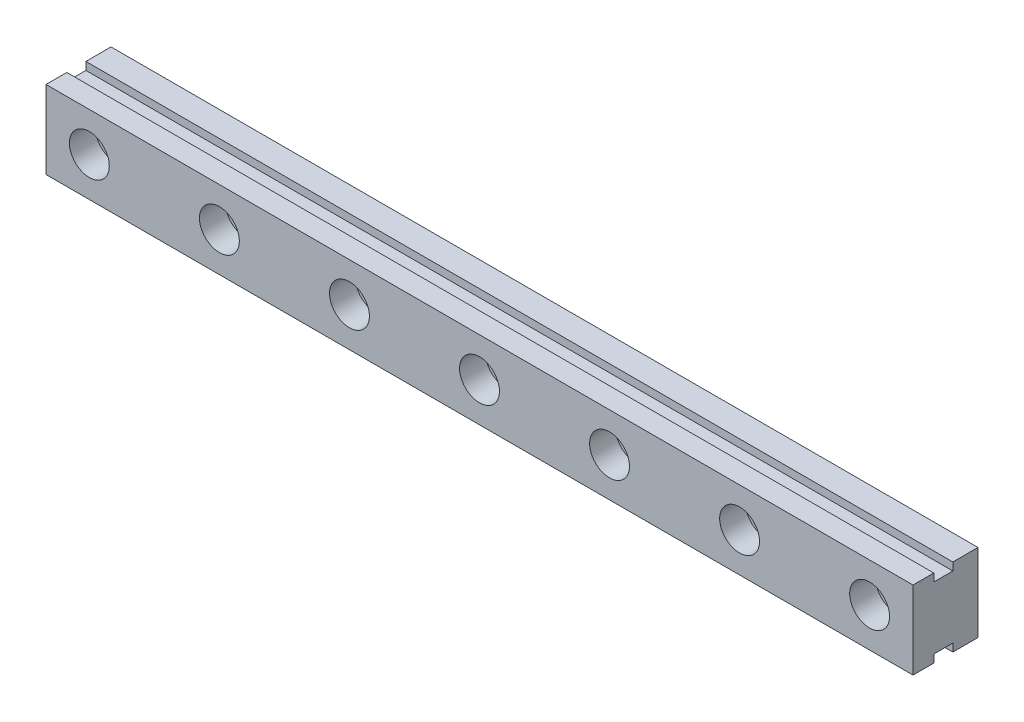
SolidWorks part; units mm, degrees
ref_plane "前视基准面" through (0, 0, 0) normal (0, 0, 1) x (1, 0, 0)
ref_plane "上视基准面" through (0, 0, 0) normal (0, 1, 0) x (1, 0, 0)
ref_plane "右视基准面" through (0, 0, 0) normal (1, 0, 0) x (0, 0, -1)
other "Configuration Table"
sketch "100 mm rail blank profile" plane through (0, 0, 0) normal (0, 0, 1) x (1, 0, 0)
  line L0 (-17, 14) -> (83, 14)
  line L1 (83, 14) -> (83, 23)
  line L2 (83, 23) -> (-17, 23)
  line L3 (-17, 23) -> (-17, 14)
extrude "100 mm rail blank" add sketch "100 mm rail blank profile" along normal blind 7.5 from offset 27.5
sketch "Longitudinal running grooves profile" plane through (0, 0, 0) normal (0, 0, 1) x (1, 0, 0)
  line L0 (-17.1, 13.5) -> (83.1, 13.5)
  line L1 (83.1, 13.5) -> (83.1, 14.9)
  line L2 (83.1, 14.9) -> (-17.1, 14.9)
  line L3 (-17.1, 14.9) -> (-17.1, 13.5)
  line L4 (-17.1, 22.1) -> (83.1, 22.1)
  line L5 (83.1, 22.1) -> (83.1, 23.5)
  line L6 (83.1, 23.5) -> (-17.1, 23.5)
  line L7 (-17.1, 23.5) -> (-17.1, 22.1)
extrude "Longitudinal running grooves" cut sketch "Longitudinal running grooves profile" along normal blind 2.2 from offset 30.4
sketch "Rail bolt clearance profile" plane through (0, 0, 0) normal (0, 0, 1) x (1, 0, 0)
  circle A0 centre (-12, 18.5) radius 1.35
  circle A1 centre (3, 18.5) radius 1.35
  circle A2 centre (18, 18.5) radius 1.35
  circle A3 centre (33, 18.5) radius 1.35
  circle A4 centre (48, 18.5) radius 1.35
  circle A5 centre (63, 18.5) radius 1.35
  circle A6 centre (78, 18.5) radius 1.35
extrude "Rail bolt clearance" cut sketch "Rail bolt clearance profile" along normal blind 7.8 from offset 27.4
sketch "Rail head recesses profile" plane through (0, 0, 0) normal (0, 0, 1) x (1, 0, 0)
  circle A0 centre (-12, 18.5) radius 2.3
  circle A1 centre (3, 18.5) radius 2.3
  circle A2 centre (18, 18.5) radius 2.3
  circle A3 centre (33, 18.5) radius 2.3
  circle A4 centre (48, 18.5) radius 2.3
  circle A5 centre (63, 18.5) radius 2.3
  circle A6 centre (78, 18.5) radius 2.3
extrude "Rail head recesses" cut sketch "Rail head recesses profile" along normal blind 3.2 from offset 32
